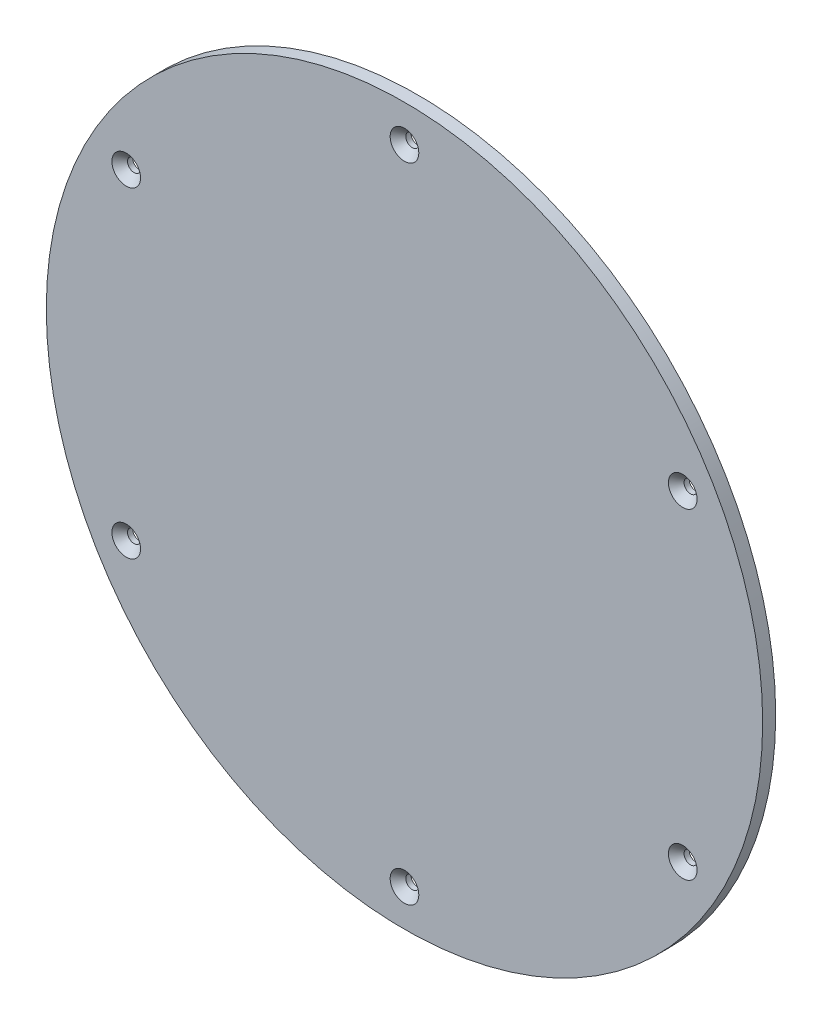
SolidWorks part; units mm, degrees
ref_plane "Front Plane" through (0, 0, 0) normal (0, 0, 1) x (1, 0, 0)
ref_plane "Top Plane" through (0, 0, 0) normal (0, 1, 0) x (1, 0, 0)
ref_plane "Right Plane" through (0, 0, 0) normal (1, 0, 0) x (0, 0, -1)
sketch "Sketch1" plane through (0, 0, 0) normal (0, 0, 1) x (1, 0, 0)
  line L0 (0, 0) -> (64.0859, 37) construction
  line L1 (0, 0) -> (0, 74) construction
  circle A0 centre (0, 0) radius 82.5
  circle A1 centre (0, 0) radius 74 construction
  circle A2 centre (0, 74) radius 1.5
  circle A3 centre (0, -74) radius 1.5
  circle A4 centre (64.0859, 37) radius 1.5
  circle A5 centre (64.0859, -37) radius 1.5
  circle A6 centre (-64.0859, -37) radius 1.5
  circle A7 centre (-64.0859, 37) radius 1.5
  dimension "D1" = 165
  dimension "D3" = 3
  dimension "D4" = 148
  dimension "D2" = 60
extrude "Boss-Extrude1" add sketch "Sketch1" along normal blind 3
chamfer "Chamfer1" distance 1.8 angle 45 6 edges at (-62.5859, 37, 3) (-62.5859, -37, 3) (1.5, -74, 3) (65.5859, -37, 3) (65.5859, 37, 3) (1.5, 74, 3)
